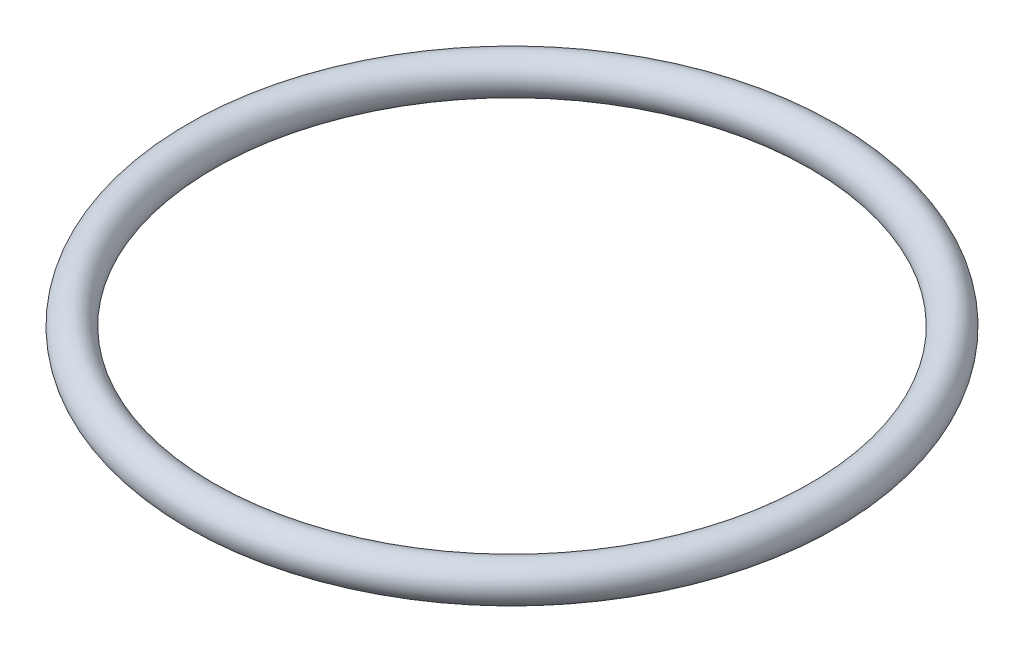
SolidWorks part; units mm, degrees
ref_plane "Płaszczyzna przednia" through (0, 0, 0) normal (0, 0, 1) x (1, 0, 0)
ref_plane "Płaszczyzna górna" through (0, 0, 0) normal (0, 1, 0) x (1, 0, 0)
ref_plane "Płaszczyzna prawa" through (0, 0, 0) normal (1, 0, 0) x (0, 0, -1)
sketch "Szkic1" plane through (0, 0, 0) normal (0, 0, 1) x (1, 0, 0)
  line L0 (0, 5.1245) -> (0, -7.9044) construction
  circle A0 centre (-25.5, -1.39) radius 1.5
  dimension "D1" = 3
  dimension "D2" = 25.5
revolve "Obrót1" add sketch "Szkic1" angle 360 about L0
